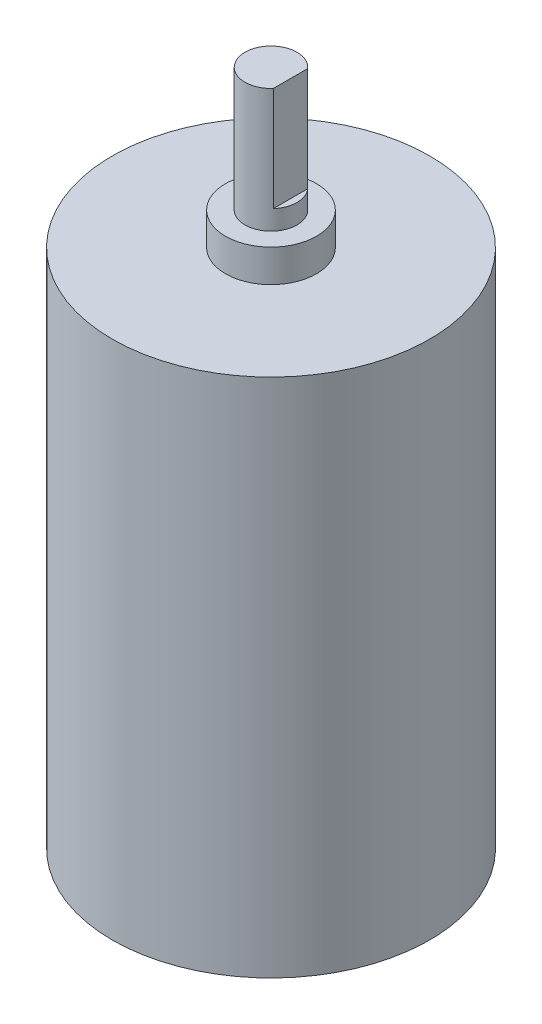
SolidWorks part; units mm, degrees
ref_plane "Front Plane" through (0, 0, 0) normal (0, 0, 1) x (1, 0, 0)
ref_plane "Top Plane" through (0, 0, 0) normal (0, 1, 0) x (1, 0, 0)
ref_plane "Right Plane" through (0, 0, 0) normal (1, 0, 0) x (0, 0, -1)
sketch "Sketch1" plane through (0, 0, 0) normal (0, 1, 0) x (1, 0, 0)
  circle A0 centre (0, 0) radius 12.2
  dimension "D1" = 24.4
extrude "Boss-Extrude1" add sketch "Sketch1" along normal blind 40
sketch "Sketch2" plane through (0, 40, 0) normal (0, 1, 0) x (1, 0, 0)
  circle A0 centre (0, 0) radius 3.5
  dimension "D1" = 7
extrude "Boss-Extrude2" add sketch "Sketch2" along normal blind 2.5
sketch "Sketch3" plane through (0, 42.5, 0) normal (0, 1, 0) x (1, 0, 0)
  circle A0 centre (0, 0) radius 2
  dimension "D1" = 4
extrude "Boss-Extrude3" add sketch "Sketch3" along normal blind 9.5
sketch "Sketch4" plane through (0, 52, 0) normal (0, 1, 0) x (1, 0, 0)
  line L1 (1.5, 2) -> (2.5, 2)
  line L2 (1.5, 2) -> (1.5, -2)
  line L3 (1.5, -2) -> (2.5, -2)
  line L4 (2.5, 2) -> (2.5, -2)
  circle A1 centre (0, 0) radius 2 construction
  circle A2 centre (0, 0) radius 2 construction
  point P4 (1.6498, 1.6019)
  point P9 (2, 2)
  dimension "D1" = 2
  dimension "D2" = 1
extrude "Cut-Extrude1" cut sketch "Sketch4" against normal blind 8
